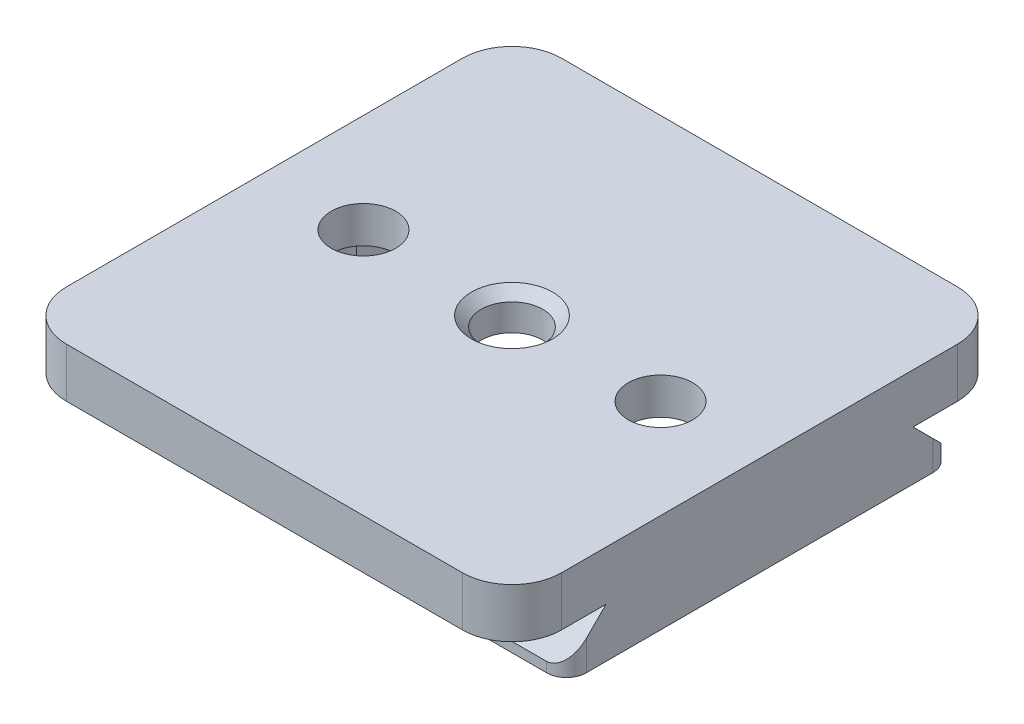
SolidWorks part; units mm, degrees
ref_plane "Front Plane" through (0, 0, 0) normal (0, 0, 1) x (1, 0, 0)
ref_plane "Top Plane" through (0, 0, 0) normal (0, 1, 0) x (1, 0, 0)
ref_plane "Right Plane" through (0, 0, 0) normal (1, 0, 0) x (0, 0, -1)
sketch "Sketch1" plane through (0, 0, 0) normal (0, 1, 0) x (1, 0, 0)
  line L1 (25, -25) -> (-25, -25)
  line L2 (25, -25) -> (25, 25)
  line L3 (25, 25) -> (-25, 25)
  line L4 (-25, -25) -> (-25, 25)
  line L5 (25, -25) -> (-25, 25) construction
  line L6 (25, 25) -> (-25, -25) construction
  point P0 (0, 0)
  dimension "D1" = 50
  dimension "D2" = 50
extrude "Boss-Extrude1" add sketch "Sketch1" along normal blind 10
sketch "Sketch4" plane through (0, 0, 0) normal (0, -1, 0) x (-1, 0, 0)
  line L0 (21, -7.2284) -> (21, -10.5)
  line L1 (-18.5, 13) -> (18.5, 13)
  line L2 (-21, 10.5) -> (-21, 7.2284)
  line L3 (-18.5, -13) -> (18.5, -13)
  line L4 (21, 10.5) -> (21, 7.2284)
  line L5 (-21, 13) -> (21, -13) construction
  line L6 (-21, -13) -> (21, 13) construction
  line L7 (-21, -7.2284) -> (-21, -10.5)
  arc A0 (19.5333, 5.3008) -> (19.5333, -5.3008) centre (21, 0) ccw
  arc A1 (-19.5333, -5.3008) -> (-19.5333, 5.3008) centre (-21, 0) ccw
  arc A2 (-21, -10.5) -> (-18.5, -13) centre (-18.5, -10.5) ccw
  arc A3 (-18.5, 13) -> (-21, 10.5) centre (-18.5, 10.5) ccw
  arc A4 (18.5, 13) -> (21, 10.5) centre (18.5, 10.5) cw
  arc A5 (18.5, -13) -> (21, -10.5) centre (18.5, -10.5) ccw
  arc A6 (-19.5333, -5.3008) -> (-21, -7.2284) centre (-19, -7.2284) ccw
  arc A7 (-21, 7.2284) -> (-19.5333, 5.3008) centre (-19, 7.2284) ccw
  arc A8 (19.5333, 5.3008) -> (21, 7.2284) centre (19, 7.2284) ccw
  arc A9 (19.5333, -5.3008) -> (21, -7.2284) centre (19, -7.2284) cw
  point P0 (0, 0)
  point P26 (-21, -5.5)
  point P33 (21, -5.5)
  dimension "D3" = 11
  dimension "D4" = 11
  dimension "D5" = 2.5
  dimension "D6" = 2
  dimension "D1" = 42
  dimension "D2" = 26
extrude "Cut-Extrude3" cut sketch "Sketch4" against normal blind 6.3
sketch "Sketch5" plane through (0, 6.3, 0) normal (0, -1, 0) x (-1, 0, 0)
  circle A0 centre (0, 0) radius 6.5
  circle A1 centre (0, 0) radius 3.1
  dimension "D1" = 13
  dimension "D2" = 6.2
extrude "Boss-Extrude2" add sketch "Sketch5" along normal blind 0.5
sketch "Sketch6" plane through (0, 0, 0) normal (0, -1, 0) x (1, 0, 0)
  line L0 (-25, -25) -> (-25, 25) construction
  circle A0 centre (-20, 0) radius 2.7
  circle A1 centre (20, 0) radius 2.7
  dimension "D1" = 5.4
  dimension "D2" = 40
  dimension "D3" = 5
extrude "Boss-Extrude3" [suppressed] add sketch "Sketch6" along normal blind 2.5
fillet "Fillet1" [suppressed] radius 0.5
sketch "Sketch8" plane through (25, 0, 0) normal (1, 0, 0) x (0, 0, -1)
  line L0 (25, 10) -> (25, 0) construction
  line L16 (-25, 0) -> (-25, 5)
  line L17 (-25, 5) -> (-15.5, 5)
  line L18 (25, 0) -> (25, 5)
  line L19 (15.5, 5) -> (25, 5)
  line L20 (-25, 0) -> (25, 0) construction
  line L22 (-20.5, 0) -> (-15.5, 5)
  line L23 (20.5, 0) -> (15.5, 5)
  line L24 (-20.5, 0) -> (-25, 0)
  line L25 (20.5, 0) -> (25, 0)
  dimension "D1" = 9.5
  dimension "D2" = 45
extrude "Cut-Extrude4" cut sketch "Sketch8" against normal through all
fillet "Fillet2" radius 5 4 edges at (25, 7.5, -25) (-25, 7.5, -25) (-25, 7.5, 25) (25, 7.5, 25)
chamfer "Chamfer1" [suppressed] distance 1 angle 45
chamfer "Chamfer2" distance 1 angle 90 2 edges at (0, 0, 20.5) (0, 0, -20.5)
fillet "Fillet3" radius 2 4 edges at (25, 0.5, -19.5) (25, 0.5, 19.5) (-25, 0.5, 19.5) (-25, 0.5, -19.5)
sketch "Sketch9" plane through (0, 6.3, 0) normal (0, -1, 0) x (-1, 0, 0)
  circle A0 centre (0, 0) radius 3.1
extrude "Cut-Extrude5" cut sketch "Sketch9" against normal through all
chamfer "Chamfer3" distance 1 angle 45 1 edges at (0, 10, -3.1)
sketch "Sketch10" plane through (0, 0, 0) normal (0, -1, 0) x (1, 0, 0)
  line L1 (-26, 9.8547) -> (26, 9.8547)
  line L2 (-26, 9.8547) -> (-26, -9.8547)
  line L3 (-26, -9.8547) -> (26, -9.8547)
  line L4 (26, 9.8547) -> (26, -9.8547)
  line L5 (-26, 9.8547) -> (26, -9.8547) construction
  line L6 (-26, -9.8547) -> (26, 9.8547) construction
  point P0 (0, 0)
  dimension "D1" = 52
extrude "Cut-Extrude6" cut sketch "Sketch10" against normal up to surface (6.3 mm away) up to face at (0, 6.3, -6.5)
sketch "Sketch12" plane through (0, 6.3, 0) normal (0, -1, 0) x (1, 0, 0)
  line L1 (25, -9.8547) -> (27, -9.8547)
  line L2 (25, -9.8547) -> (25, 9.8547)
  line L3 (25, 9.8547) -> (27, 9.8547)
  line L4 (27, -9.8547) -> (27, 9.8547)
  line L5 (26, 9.8547) -> (26, -9.8547) construction
  line L6 (25, 0) -> (27, 0) construction
  line L7 (-25, -9.8547) -> (-27, -9.8547)
  line L8 (-25, -9.8547) -> (-25, 9.8547)
  line L9 (-25, 9.8547) -> (-27, 9.8547)
  line L10 (-27, -9.8547) -> (-27, 9.8547)
  line L11 (-26, 9.8547) -> (-26, -9.8547) construction
  line L12 (-25, 0) -> (-27, 0) construction
  circle A1 centre (0, 0) radius 3.1 construction
  point P4 (0, 0)
  point P357 (-26, 0)
  point P444 (26, 0)
  dimension "D1" = 27
extrude "Boss-Extrude4" [suppressed] add sketch "Sketch12" against normal up to surface (3.7 mm away)
sketch "Sketch14" plane through (0, 6.3, 0) normal (0, -1, 0) x (1, 0, 0)
  line L0 (0, -6.875) -> (0, 6.875) construction
  circle A0 centre (15, 0) radius 3.25
  circle A1 centre (-15, 0) radius 3.25
  dimension "D1" = 6.5
  dimension "D2" = 15
  dimension "D3" = 15
extrude "Cut-Extrude7" cut sketch "Sketch14" against normal blind 10 contours A1 | A0
sketch "Sketch15" plane through (0, 6.3, 0) normal (0, -1, 0) x (-1, 0, 0)
  line L1 (-21, 9.8547) -> (-25, 9.8547)
  line L2 (-21, 9.8547) -> (-21, -9.8547)
  line L3 (-21, -9.8547) -> (-25, -9.8547)
  line L4 (-25, 9.8547) -> (-25, -9.8547)
  line L5 (-23, -9.8547) -> (-23, 9.8547) construction
  line L6 (-21, 0) -> (-25, 0) construction
  line L7 (21, 9.8547) -> (25, 9.8547)
  line L8 (21, 9.8547) -> (21, -9.8547)
  line L9 (21, -9.8547) -> (25, -9.8547)
  line L10 (25, 9.8547) -> (25, -9.8547)
  line L11 (23, -9.8547) -> (23, 9.8547) construction
  line L12 (21, 0) -> (25, 0) construction
  point P212 (23, 0)
  point P280 (-23, 0)
extrude "Boss-Extrude5" add sketch "Sketch15" along normal up to surface (6.3 mm away) up to face at (0, 0, -13.5236)
sketch "Sketch16" plane through (0, 6.3, 0) normal (0, -1, 0) x (-1, 0, 0)
  circle A0 centre (-15, 0) radius 8
  circle A1 centre (15, 0) radius 8
extrude "Cut-Extrude8" cut sketch "Sketch16" along normal blind 10
